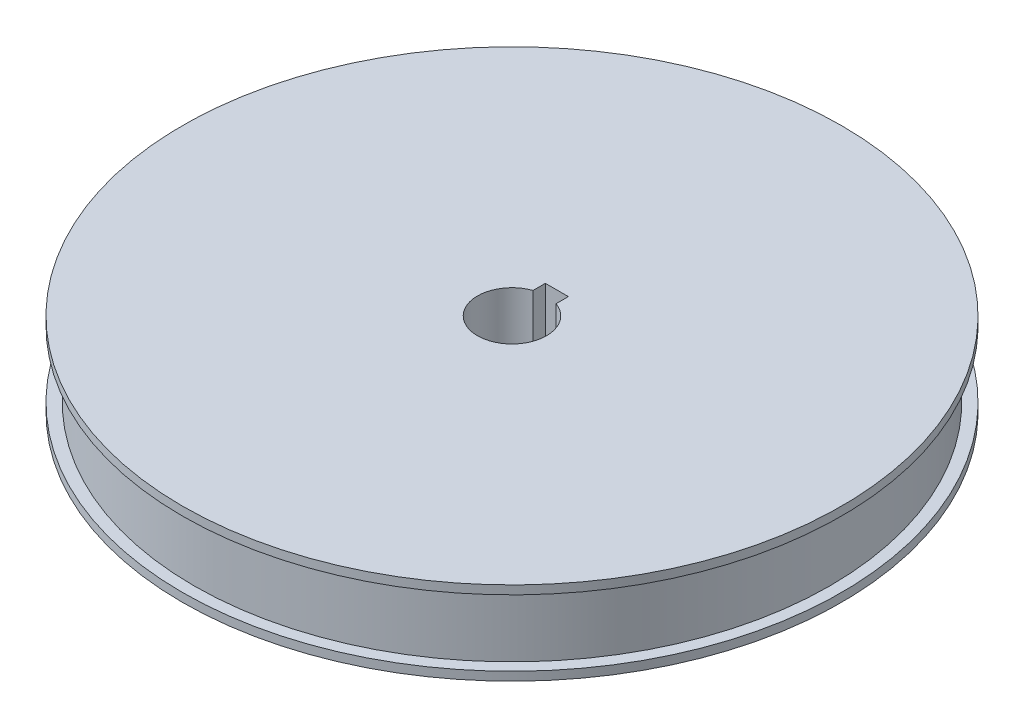
SolidWorks part; units mm, degrees
ref_plane "Front" through (0, 0, 0) normal (0, 0, 1) x (1, 0, 0)
ref_plane "Top" through (0, 0, 0) normal (0, 1, 0) x (1, 0, 0)
ref_plane "Right" through (0, 0, 0) normal (1, 0, 0) x (0, 0, -1)
sketch "Sketch1" plane through (0, 0, 0) normal (1, 0, 0) x (0, 0, -1)
  line L0 (0, 10.3155) -> (0, -12.6924) construction
  line L1 (-13.3377, 0) -> (15.1571, 0) construction
  line L2 (55.295, -5.75) -> (55.295, 5.75)
  line L3 (57.295, 5.75) -> (57.295, 7.25)
  line L4 (57.295, 7.25) -> (6, 7.25)
  line L5 (55.295, 5.75) -> (57.295, 5.75)
  line L6 (6, 7.25) -> (6, -7.25)
  line L7 (55.295, -5.75) -> (57.295, -5.75)
  line L8 (57.295, -5.75) -> (57.295, -7.25)
  line L9 (57.295, -7.25) -> (6, -7.25)
  point P11 (55.295, 0)
  point P15 (6, 0)
  dimension "D1" = 1.5
  dimension "D2" = 7.25
  dimension "D3" = 57.295
  dimension "D4" = 2
  dimension "D5" = 6
revolve "Revolve1" add sketch "Sketch1" angle 360 about L0
sketch "Sketch3" [suppressed] plane through (0, 7, 0) normal (0, 1, 0) x (1, 0, 0)
  circle A0 centre (0, 0) radius 6 construction
  circle A1 centre (0, 0) radius 6
  circle A3 centre (0, 0) radius 5
  dimension "D1" = 1
extrude "Boss-Extrude1" [suppressed] add sketch "Sketch3" against normal up to surface (14 mm away)
sketch "Sketch2" plane through (0, 7.25, 0) normal (0, 1, 0) x (1, 0, 0)
  line L0 (0, 17.5613) -> (0, -19.1998) construction
  line L1 (-24.037, 0) -> (25.1355, 0) construction
  line L3 (-2, 3.5) -> (2, 3.5)
  line L4 (-2, 3.5) -> (-2, 7.8)
  line L5 (-2, 7.8) -> (2, 7.8)
  line L6 (2, 3.5) -> (2, 7.8)
  point P9 (0, 7.8)
  dimension "D1" = 4.3
  dimension "D2" = 4
  dimension "D3" = 3.5
extrude "Cut-Extrude1" cut sketch "Sketch2" against normal through all
sketch "Sketch4" [suppressed] plane through (0, 7, 0) normal (0, 1, 0) x (1, 0, 0)
  line L0 (0, 0) -> (0, 11.0035) construction
  line L1 (-1.5, 3.2) -> (1.5, 3.2)
  line L2 (-1.5, 3.2) -> (-1.5, 6.4)
  line L3 (-1.5, 6.4) -> (1.5, 6.4)
  line L4 (1.5, 3.2) -> (1.5, 6.4)
  point P7 (0, 6.4)
  dimension "D1" = 3
  dimension "D2" = 3.2
  dimension "D3" = 3.2
extrude "Cut-Extrude2" [suppressed] cut sketch "Sketch4" against normal through all
sketch "Sketch5" [suppressed] plane through (0, 7, 0) normal (0, 1, 0) x (1, 0, 0)
  circle A0 centre (0, 0) radius 5
  circle A1 centre (0, 0) radius 6 construction
  circle A2 centre (0, 0) radius 6
  dimension "D1" = 10
extrude "Boss-Extrude2" [suppressed] add sketch "Sketch5" against normal up to surface (14 mm away)
sketch "Sketch6" [suppressed] plane through (0, 7, 0) normal (0, 1, 0) x (1, 0, 0)
  circle A0 centre (0, 0) radius 8
  circle A1 centre (0, 0) radius 5 construction
  circle A2 centre (0, 0) radius 5
  dimension "D1" = 3
extrude "Boss-Extrude3" [suppressed] add sketch "Sketch6" along normal blind 10
